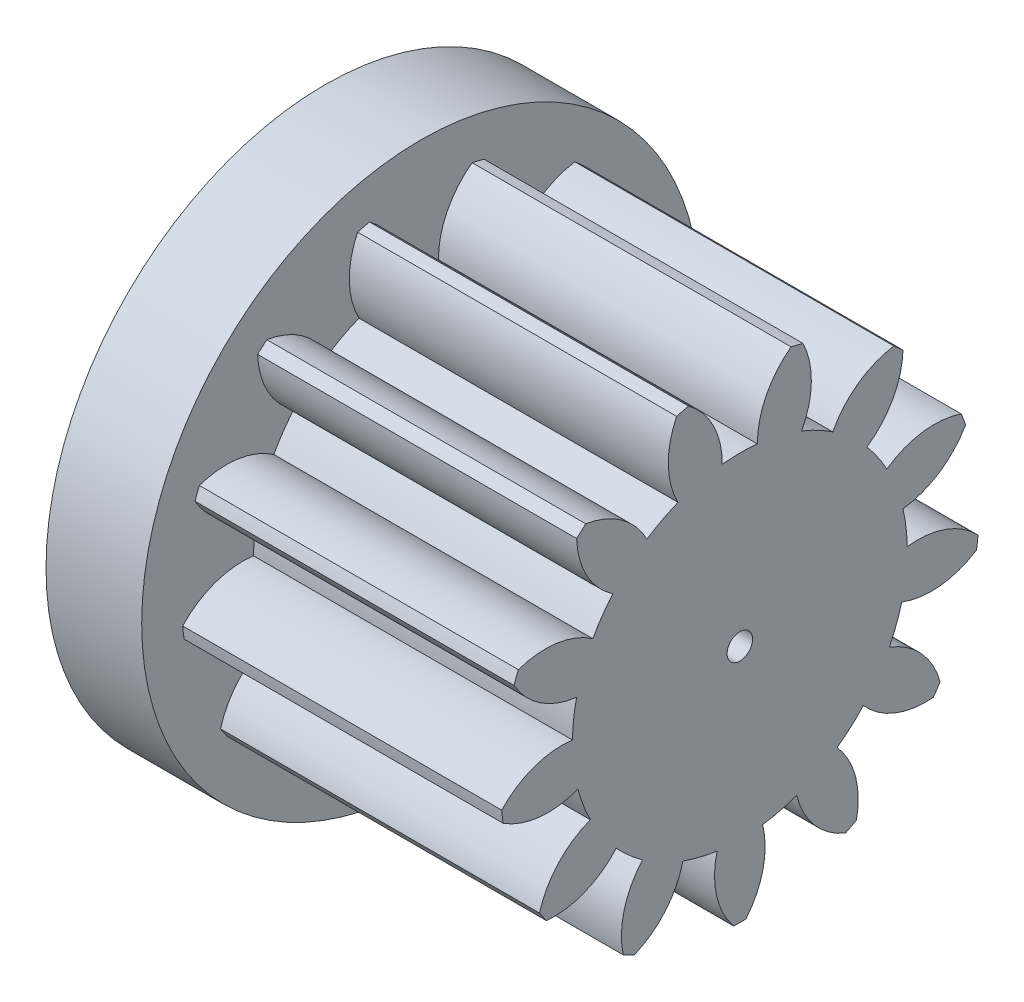
SolidWorks part; units mm, degrees
ref_plane "Plane1" through (0, 0, 0) normal (0, 0, 1) x (1, 0, 0)
ref_plane "Plane2" through (0, 0, 0) normal (0, 1, 0) x (1, 0, 0)
ref_plane "Plane3" through (0, 0, 0) normal (1, 0, 0) x (0, 0, -1)
sketch "HoldingSke" plane through (0, 0, 0) normal (0, 1, 0) x (1, 0, 0)
  line L0 (0, 0) -> (0.9744, -0.225)
  line L1 (-15, 0) -> (100, 0) construction
  line L2 (0, 0) -> (-2.1039, 2.3779)
  line L3 (0, 0) -> (-11.863, 4.5341)
  line L4 (0, 0) -> (8.4147, 1.9427)
  line L5 (0, 0) -> (-46.8476, -17.4728)
  line L6 (0, 0) -> (-8.2896, -5.593)
  line L7 (-2.1039, 2.3779) -> (8.6586, 51.2059)
  line L8 (-76.2, 54.61) -> (-76.1, 54.61)
  line L9 (-71.009, 38.7566) -> (-53.1078, 45.2721)
  line L10 (-76.2, 71.12) -> (104.1128, 71.12)
  line L11 (0, 0) -> (-10, 0)
  line L12 (-76.2, 101.6) -> (-76.162, 101.6)
  line L13 (24.9733, 27.94) -> (52.9518, 28.4284)
  line L14 (24.9733, 27.94) -> (24.9743, 27.94)
  line L15 (24.9733, 27.94) -> (100.4006, 29.5858)
  line L16 (-63.627, -1) -> (-12.827, -1)
  circle A0 centre (0, 0) radius 0.4
  circle A1 centre (0, 0) radius 5.249
  circle A2 centre (0, 0) radius 37.5
  circle A3 centre (0, 0) radius 0.4
  dimension "MHD" = 10.498
  dimension "Hub_dia" = 75
  dimension "Bore" = 0.8
  dimension "MBD" = 0.8
  dimension "Num_teeth" = 13
  dimension "Pitch" = 1
  dimension "Overall_len" = 50
  dimension "Show_teeth" = 13
  dimension "Thickness" = 10
  dimension "OAL" = 50.0001
  dimension "T_dim" = 0.1
  dimension "Ap" = 20
  dimension "H" = 19.05
  dimension "Pitch_radius" = 180.3128
  dimension "Width" = 10
  dimension "Backlash" = 0.038
  dimension "Addendum_fac" = 1
  dimension "Dedendum_fac" = 1.25
  dimension "Clearance_fac" = 0.25
  dimension "Dedendum_add" = 0.001
  dimension "Module" = 1
sketch "BasProSke" plane through (0, 0, 0) normal (0, 1, 0) x (1, 0, 0)
  line L0 (-10, 0) -> (60, 0) construction
  line L1 (0, 0) -> (0, 7.5)
  line L2 (0, 0) -> (10, 0)
  line L3 (10, 0) -> (10, 7.5)
  line L4 (10, 7.5) -> (0, 7.5)
  dimension "Thickness" = 10
  dimension "Diameter" = 15
revolve "Base-Revolve" add sketch "BasProSke" angle 360 about L0
sketch "TooCutSke" plane through (0, 0, 0) normal (1, 0, 0) x (0, 0, -1)
  line L1 (0, 0) -> (0, 107) construction
  line L2 (0, 0) -> (-0.8499, 6.4442) construction
  line L3 (0, 0) -> (-3.0921, 12.5452) construction
  line L4 (-0.8499, 6.4442) -> (-1.5461, 6.2726) construction
  arc A0 (0.5505, 5.2201) -> (-0.5505, 5.2201) centre (0, 0) ccw
  arc A1 (1.6352, 7.3456) -> (-1.6352, 7.3456) centre (0, 0) ccw
  circle A2 centre (0, 0) radius 6.5 construction
  circle A3 centre (0, 0) radius 6.108 construction
  arc A4 (-0.5505, 5.2201) -> (-1.6352, 7.3456) centre (-3.1505, 5.2328) ccw
  arc A5 (1.6352, 7.3456) -> (0.5505, 5.2201) centre (3.1505, 5.2328) ccw
  dimension "Root_dia" = 10.498
  dimension "Overcut_dia" = 15.0508
  dimension "Pitch_dia" = 13
  dimension "Base_dia" = 12.216
  dimension "Flank_rad" = 2.6
  dimension "Half_ang" = 13.846
  dimension "Half_CT" = 0.717
extrude "ToothCut" cut sketch "TooCutSke" along normal through all
fillet "Breaks" [suppressed] radius 0.02
fillet "RootFillets" [suppressed] radius 0.251
pattern_circular "TeethCuts" count 13 every 27.692 about axis through (-10, 0, 0) along (1, 0, 0) of "ToothCut", "RootFillets", "Breaks"
sketch "HubNeaOneSke" plane through (0, 0, 0) normal (-1, 0, 0) x (0, 0, 1)
  circle A0 centre (0, 0) radius 5.249
  dimension "Diameter" = 10.498
extrude "HubNearOne" [suppressed] add sketch "HubNeaOneSke" along normal blind 40.0001
sketch "HubNeaBotSke" plane through (0, 0, 0) normal (-1, 0, 0) x (0, 0, 1)
  circle A0 centre (0, 0) radius 5.249
  dimension "Diameter" = 10.498
extrude "HubNearBoth" [suppressed] add sketch "HubNeaBotSke" along normal blind 20
ref_plane "FarPln" through (10, 0, 0) normal (1, 0, 0) x (0, 0, -1)
sketch "HubFarSke" plane through (10, 0, 0) normal (1, 0, 0) x (0, 0, -1)
  circle A0 centre (0, 0) radius 5.249
  dimension "Diameter" = 10.498
extrude "HubFar" [suppressed] add sketch "HubFarSke" along normal blind 20
sketch "BorSke" plane through (0, 0, 0) normal (1, 0, 0) x (0, 0, -1)
  circle A0 centre (0, 0) radius 0.4
  dimension "Diameter" = 0.8
extrude "Bore" cut sketch "BorSke" along normal mid plane 100.0001
sketch "KeySke" plane through (0, 0, 0) normal (1, 0, 0) x (0, 0, -1)
  line L0 (-0.05, 0) -> (-0.05, 0.5)
  line L1 (-0.05, 0.5) -> (0.05, 0.5)
  line L2 (0.05, 0.5) -> (0.05, 0)
  line L3 (0, 0) -> (0, 34) construction
  line L4 (-0.05, 0) -> (0.05, 0)
  dimension "Offset" = 0.5
  dimension "Width" = 0.1
extrude "Keyway" [suppressed] cut sketch "KeySke" along normal mid plane 100.0001
pattern_circular "Keyway2" [suppressed] count 2 every 90 about axis through (-10, 0, 0) along (1, 0, 0)
sketch "Sketch1" plane through (0, 0, 0) normal (-1, 0, 0) x (0, 0, 1)
  circle A0 centre (0, 0) radius 8.75
  dimension "D1" = 17.5
extrude "Boss-Extrude1" add sketch "Sketch1" along normal blind 3
sketch "Sketch5" plane through (10, 0, 0) normal (1, 0, 0) x (0, 0, -1)
  circle A0 centre (2.286, 4.659) radius 0.0594
  circle A1 centre (0, 0) radius 5.249
sketch "Sketch6" plane through (-3, 0, 0) normal (-1, 0, 0) x (0, 0, 1)
  circle A3 centre (-8.0167, -1.7243) radius 0.5
  circle A4 centre (-8.0167, -1.7243) radius 0.5
  dimension "D2" = 0
extrude "Cut-Extrude1" cut sketch "Sketch6" against normal blind 2
pattern_circular "CirPattern1" count 6 over 360 about axis through (0, 0, 0) along (1, 0, 0) of "Cut-Extrude1"
equation "' \"Module@HoldingSke\" = 6.35"
equation "' \"Num_teeth@HoldingSke\" = 12"
equation "' \"Ap@HoldingSke\" =  20"
equation "' \"Ap@HoldingSke\" = 20"
equation "' \"Width@HoldingSke\" = 0.5 * 25.4"
equation "' \"Hub_dia@HoldingSke\"= 1 * 25.4"
equation "' \"Hub_dia@HoldingSke\" = 1 * 25.4"
equation "' \"Overall_len@HoldingSke\" = 1.0 * 25.4"
equation "' \"Bore@HoldingSke\" = 0.75 * 25.4"
equation "' \"T_dim@HoldingSke\" = 0.1 * 25.4"
equation "' \"Width@KeySke\" = 0.25 * 25.4"
equation "' \"Show_teeth@HoldingSke\" = 13"
equation "' \"Backlash@HoldingSke\" = 0.009 * 25.4"
equation "' \"Addendum_fac@HoldingSke\" = 1.0"
equation "' \"Dedendum_fac@HoldingSke\" = 1.25"
equation "' \"Dedendum_add@HoldingSke\" = 0.00005 * 25.4"
equation "' \"Clearance_fac@HoldingSke\" = 0.25"
equation "\"Pitch@HoldingSke\" = 1 / \"Module@HoldingSke\""
equation "\"Overcut_dia@TooCutSke\" = (\"Num_teeth@HoldingSke\" + 2 * \"Addendum_fac@HoldingSke\") / \"Pitch@HoldingSke\" + 0.002 * 25.4"
equation "\"Pitch_dia@TooCutSke\" = \"Num_teeth@HoldingSke\" / \"Pitch@HoldingSke\""
equation "\"Base_dia@TooCutSke\" = \"Num_teeth@HoldingSke\" / \"Pitch@HoldingSke\" * cos((\"Ap@HoldingSke\"  * 3.14159265 / 180))"
equation "\"Root_dia@TooCutSke\" = (\"Num_teeth@HoldingSke\" + 2) / \"Pitch@HoldingSke\" - 2 * (\"Addendum_fac@HoldingSke\" + \"Dedendum_fac@HoldingSke\") / \"Pitch@HoldingSke\" - \"Dedendum_add@HoldingSke\" * 2"
equation "\"Half_ang@TooCutSke\" = 180 / \"Num_teeth@HoldingSke\""
equation "\"Half_CT@TooCutSke\" = \"Num_teeth@HoldingSke\" / \"Pitch@HoldingSke\" * sin((3.14159265 / 2 / \"Num_teeth@HoldingSke\")) / 2 - 7 * \"Backlash@HoldingSke\" / 4"
equation "\"Flank_rad@TooCutSke\" = \"Num_teeth@HoldingSke\" / \"Pitch@HoldingSke\" / 5"
equation "\"Radius@RootFillets\" = \"Clearance_fac@HoldingSke\" / \"Pitch@HoldingSke\" + \"Dedendum_add@HoldingSke\""
equation "\"Break_rad@Breaks\" = 0.02 / \"Pitch@HoldingSke\""
equation "\"Thickness@HoldingSke\" = \"Width@HoldingSke\""
equation "\"OAL@HoldingSke\" = \"Thickness@HoldingSke\""
equation "\"MHD@HoldingSke\" = (\"Num_teeth@HoldingSke\" + 2) / \"Pitch@HoldingSke\" - 2 * (\"Addendum_fac@HoldingSke\" + \"Dedendum_fac@HoldingSke\")  / \"Pitch@HoldingSke\" - \"Dedendum_add@HoldingSke\" * 2"
equation "\"MBD@HoldingSke\" = (\"Num_teeth@HoldingSke\" + 2) / \"Pitch@HoldingSke\" - 2 * (\"Addendum_fac@HoldingSke\" + \"Dedendum_fac@HoldingSke\")  / \"Pitch@HoldingSke\" - \"Dedendum_add@HoldingSke\" * 2 - 0.002 * 25.4"
equation "\"MHD@HoldingSke\" = ((sgn( \"MHD@HoldingSke\" - \"Hub_dia@HoldingSke\" )-1)*( \"MHD@HoldingSke\" - \"Hub_dia@HoldingSke\" ))/-2+ \"Hub_dia@HoldingSke\""
equation "\"MBD@HoldingSke\" = ((sgn( \"MBD@HoldingSke\" - \"Bore@HoldingSke\" )-1)*( \"MBD@HoldingSke\" - \"Bore@HoldingSke\" ))/-2+ \"Bore@HoldingSke\""
equation "\"OAL@HoldingSke\" = ((sgn( \"OAL@HoldingSke\" - \"Overall_len@HoldingSke\" )+1)*( \"OAL@HoldingSke\" - \"Overall_len@HoldingSke\" ))/2 + \"Overall_len@HoldingSke\" + 0.000002 * 25.4"
equation "\"Num_teeth@TeethCuts\" = int( \"Show_teeth@HoldingSke\" ) + 1"
equation "\"Num_teeth@TeethCuts\" = ((sgn( \"Num_teeth@TeethCuts\" - \"Num_teeth@HoldingSke\" )-1)*( \"Num_teeth@TeethCuts\" - \"Num_teeth@HoldingSke\" ))/-2+ \"Num_teeth@HoldingSke\""
equation "\"Num_teeth@TeethCuts\" = ((sgn( \"Num_teeth@TeethCuts\" - 2.0)+1)*( \"Num_teeth@TeethCuts\" - 2.0))/2 +2.0"
equation "\"Angle@TeethCuts\" = 360.0 / \"Num_teeth@HoldingSke\""
equation "\"Diameter@BasProSke\" = (\"Num_teeth@HoldingSke\" + 2 * \"Addendum_fac@HoldingSke\") / \"Pitch@HoldingSke\""
equation "\"Thickness@BasProSke\"  = \"Thickness@HoldingSke\""
equation "' \"Fillet_rad@BasProSke\" =  \"Thickness@HoldingSke\" * 0.05"
equation "' \"Fillet_rad@BasProSke\" = \"Thickness@HoldingSke\" * 0.05"
equation "\"MHD@HoldingSke\" = ((sgn( \"MHD@HoldingSke\" - \"Root_dia@TooCutSke\" )-1)*( \"MHD@HoldingSke\" - \"Root_dia@TooCutSke\" ))/-2+ \"Root_dia@TooCutSke\""
equation "\"Diameter@HubNeaOneSke\" = \"MHD@HoldingSke\""
equation "\"Length@HubNearOne\" = \"OAL@HoldingSke\" - \"Thickness@BasProSke\""
equation "\"Diameter@HubNeaBotSke\" = \"MHD@HoldingSke\""
equation "\"Length@HubNearBoth\" = ( \"OAL@HoldingSke\" - \"Thickness@BasProSke\" ) / 2.0"
equation "\"Thickness@FarPln\" = \"Thickness@BasProSke\""
equation "\"Diameter@HubFarSke\" = \"MHD@HoldingSke\""
equation "\"Length@HubFar\" = ( \"OAL@HoldingSke\" - \"Thickness@BasProSke\" ) / 2.0"
equation "\"Diameter@BorSke\" = \"MBD@HoldingSke\""
equation "\"D1@Bore\" = \"OAL@HoldingSke\" * 2.0"
equation "\"D1@Keyway\" = \"OAL@HoldingSke\" * 2.0"
equation "\"Offset@KeySke\" = \"T_dim@HoldingSke\" + \"MBD@HoldingSke\" / 2.0"
